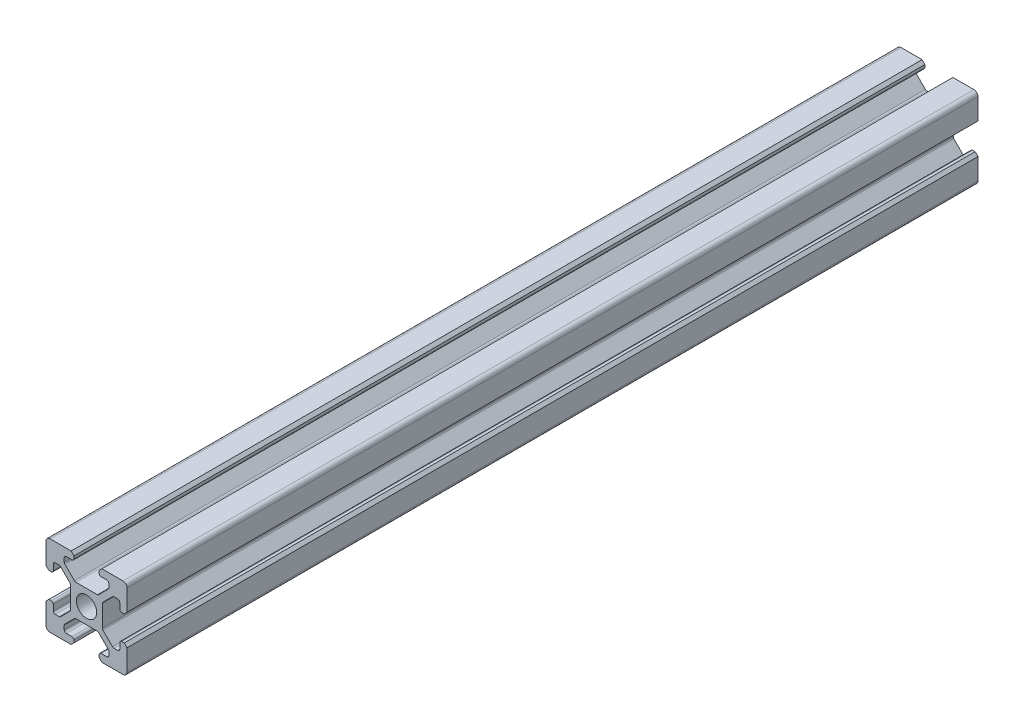
SolidWorks part; units mm, degrees
material "1060 Alloy"
ref_plane "Front Plane" through (0, 0, 0) normal (0, 0, 1) x (1, 0, 0)
ref_plane "Top Plane" through (0, 0, 0) normal (0, 1, 0) x (1, 0, 0)
ref_plane "Right Plane" through (0, 0, 0) normal (1, 0, 0) x (0, 0, -1)
sketch "Sketch1" plane through (0, 0, 0) normal (0, 0, 1) x (1, 0, 0)
  line L0 (3.9, -2.8393) -> (6.5607, -5.5)
  line L1 (-10, 10) -> (10, 10) construction
  line L2 (-10, 10) -> (-10, -10) construction
  line L3 (-10, -10) -> (10, -10) construction
  line L4 (10, 10) -> (10, -10) construction
  line L5 (-10, 10) -> (10, -10) construction
  line L6 (-10, -10) -> (10, 10) construction
  line L7 (-3.9, -3.9) -> (3.9, -3.9) construction
  line L8 (-3.9, -3.9) -> (-3.9, 3.9) construction
  line L9 (-3.9, 3.9) -> (3.9, 3.9) construction
  line L10 (3.9, -3.9) -> (3.9, 3.9) construction
  line L11 (-3.9, -3.9) -> (3.9, 3.9) construction
  line L12 (-3.9, 3.9) -> (3.9, -3.9) construction
  line L13 (-10, 10) -> (-5.5, 10) construction
  line L14 (-10, 10) -> (-10, 5.5) construction
  line L15 (-10, 5.5) -> (-5.5, 5.5) construction
  line L16 (-5.5, 10) -> (-5.5, 5.5) construction
  line L17 (10, 10) -> (5.5, 10) construction
  line L18 (10, 10) -> (10, 5.5) construction
  line L19 (10, 5.5) -> (5.5, 5.5) construction
  line L20 (5.5, 10) -> (5.5, 5.5) construction
  line L21 (-10, -10) -> (-5.5, -10) construction
  line L22 (-10, -10) -> (-10, -5.5) construction
  line L23 (-10, -5.5) -> (-5.5, -5.5) construction
  line L24 (-5.5, -10) -> (-5.5, -5.5) construction
  line L25 (10, -10) -> (5.5, -10) construction
  line L26 (10, -10) -> (10, -5.5) construction
  line L27 (10, -5.5) -> (5.5, -5.5) construction
  line L28 (5.5, -10) -> (5.5, -5.5) construction
  line L29 (2.8393, -3.9) -> (5.5, -6.5607)
  line L30 (-5.5, 6.5607) -> (-2.8393, 3.9)
  line L31 (-6.5607, 5.5) -> (-3.9, 2.8393)
  line L32 (5.5, 6.5607) -> (2.8393, 3.9)
  line L33 (6.5607, 5.5) -> (3.9, 2.8393)
  line L34 (-6.5607, -5.5) -> (-3.9, -2.8393)
  line L35 (-5.5, -6.5607) -> (-2.8393, -3.9)
  line L36 (-2.8393, 3.9) -> (2.8393, 3.9)
  line L37 (-3.9, 2.8393) -> (-3.9, -2.8393)
  line L38 (-2.8393, -3.9) -> (2.8393, -3.9)
  line L39 (3.9, -2.8393) -> (3.9, 2.8393)
  line L40 (5.5, 6.5607) -> (5.5, 8.2007)
  line L41 (5.5, 8.2007) -> (3.1, 8.2007)
  line L42 (3.1, 8.2007) -> (3.1, 9.3)
  line L43 (3.1, 9.3) -> (3.8, 10)
  line L44 (3.8, 10) -> (10, 10)
  line L45 (10, 10) -> (10, 3.8)
  line L46 (10, 3.8) -> (9.3, 3.1)
  line L47 (9.3, 3.1) -> (8.2007, 3.1)
  line L48 (8.2007, 3.1) -> (8.2007, 5.5)
  line L49 (8.2007, 5.5) -> (6.5607, 5.5)
  line L50 (3.1, -8.2007) -> (5.5, -8.2007)
  line L51 (3.1, -9.3) -> (3.1, -8.2007)
  line L52 (3.8, -10) -> (3.1, -9.3)
  line L53 (10, -10) -> (3.8, -10)
  line L54 (10, -3.8) -> (10, -10)
  line L55 (9.3, -3.1) -> (10, -3.8)
  line L56 (8.2007, -3.1) -> (9.3, -3.1)
  line L57 (8.2007, -5.5) -> (8.2007, -3.1)
  line L58 (6.5607, -5.5) -> (8.2007, -5.5)
  line L59 (5.5, -8.2007) -> (5.5, -6.5607)
  line L60 (-8.2007, -3.1) -> (-8.2007, -5.5)
  line L61 (-9.3, -3.1) -> (-8.2007, -3.1)
  line L62 (-10, -3.8) -> (-9.3, -3.1)
  line L63 (-10, -10) -> (-10, -3.8)
  line L64 (-3.8, -10) -> (-10, -10)
  line L65 (-3.1, -9.3) -> (-3.8, -10)
  line L66 (-3.1, -8.2007) -> (-3.1, -9.3)
  line L67 (-5.5, -8.2007) -> (-3.1, -8.2007)
  line L68 (-5.5, -6.5607) -> (-5.5, -8.2007)
  line L69 (-8.2007, -5.5) -> (-6.5607, -5.5)
  line L70 (-3.1, 8.2007) -> (-5.5, 8.2007)
  line L71 (-3.1, 9.3) -> (-3.1, 8.2007)
  line L72 (-3.8, 10) -> (-3.1, 9.3)
  line L73 (-10, 10) -> (-3.8, 10)
  line L74 (-10, 3.8) -> (-10, 10)
  line L75 (-9.3, 3.1) -> (-10, 3.8)
  line L76 (-8.2007, 3.1) -> (-9.3, 3.1)
  line L77 (-8.2007, 5.5) -> (-8.2007, 3.1)
  line L78 (-6.5607, 5.5) -> (-8.2007, 5.5)
  line L79 (-5.5, 8.2007) -> (-5.5, 6.5607)
  circle A0 centre (0, 0) radius 2.5
  point P83 (0, 0)
  dimension "D1" = 5
  dimension "D2" = 20
  dimension "D3" = 7.8
  dimension "D4" = 4.5
  dimension "D5" = 1.5
  dimension "D6" = 0.75
  dimension "D7" = 1.5
  dimension "D8" = 0.75
  dimension "D9" = 1.5
  dimension "D10" = 0.75
  dimension "D11" = 1.5
  dimension "D12" = 0.75
  dimension "D13" = 1.64
  dimension "D14" = 45
  dimension "D15" = 3.1
  dimension "D16" = 6.2
  dimension "D17" = 6.2
  dimension "D18" = 3.1
  dimension "D19" = 4
extrude "Boss-Extrude1" add sketch "Sketch1" along normal mid plane 210 contours L79 L70 L71 L72 L73 L74 L75 L76 L77 L78 L31 L37 L34 L69 L60 L61 L62 L63 L64 L65 L66 L67 L68 L35 L38 L29 L59 L50 L51 L52 L53 L54 L55 L56 L57 L58 L0 L39 L33 L49 L48 L47 L46 L45 L44 L43 L42 L41 L40 L32 L36
fillet "Fillet1" radius 0.5 8 edges at (2.8393, -3.9, 0) (-2.8393, -3.9, 0) (-3.9, 2.8393, 0) (-3.9, -2.8393, 0) (3.9, -2.8393, 0) (3.9, 2.8393, 0) (2.8393, 3.9, 0) (-2.8393, 3.9, 0)
fillet "Fillet2" radius 0.5 24 edges at (-8.2007, -3.1, 0) (-8.2007, -5.5, 0) (-6.5607, -5.5, 0) (-3.1, -8.2007, 0) (-5.5, -8.2007, 0) (-5.5, -6.5607, 0) (3.1, -8.2007, 0) (5.5, -6.5607, 0) (5.5, -8.2007, 0) (8.2007, -5.5, 0) (8.2007, -3.1, 0) (6.5607, -5.5, 0) (-8.2007, 3.1, 0) (-6.5607, 5.5, 0) (-8.2007, 5.5, 0) (6.5607, 5.5, 0) (8.2007, 5.5, 0) (8.2007, 3.1, 0) (5.5, 6.5607, 0) (5.5, 8.2007, 0) (3.1, 8.2007, 0) (-3.1, 8.2007, 0) (-5.5, 8.2007, 0) (-5.5, 6.5607, 0)
fillet "Fillet3" radius 1 4 edges at (-10, 10, 0) (-10, -10, 0) (10, 10, 0) (10, -10, 0)
